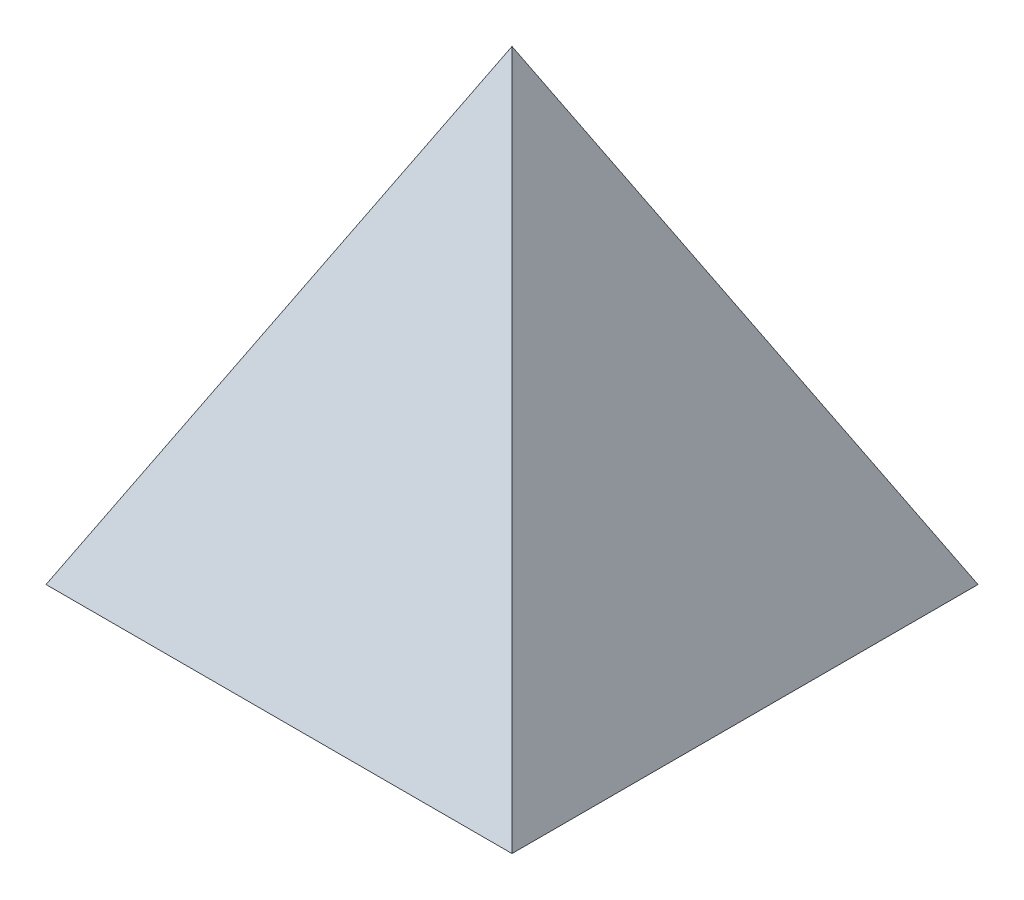
SolidWorks part; units mm, degrees
ref_plane "Front Plane" through (0, 0, 0) normal (0, 0, 1) x (1, 0, 0)
ref_plane "Top Plane" through (0, 0, 0) normal (0, 1, 0) x (1, 0, 0)
ref_plane "Right Plane" through (0, 0, 0) normal (1, 0, 0) x (0, 0, -1)
sketch "Sketch1" plane through (0, 0, 0) normal (0, 1, 0) x (1, 0, 0)
  line L1 (-250, -250) -> (250, -250)
  line L2 (-250, -250) -> (-250, 250)
  line L3 (-250, 250) -> (250, 250)
  line L4 (250, -250) -> (250, 250)
  line L5 (-250, -250) -> (250, 250) construction
  line L6 (-250, 250) -> (250, -250) construction
  point P0 (0, 0)
  point P6 (-250, 250)
  dimension "D1" = 500
  dimension "D2" = 500
extrude "Boss-Extrude2" add sketch "Sketch1" along normal blind 500 draft 26.565
